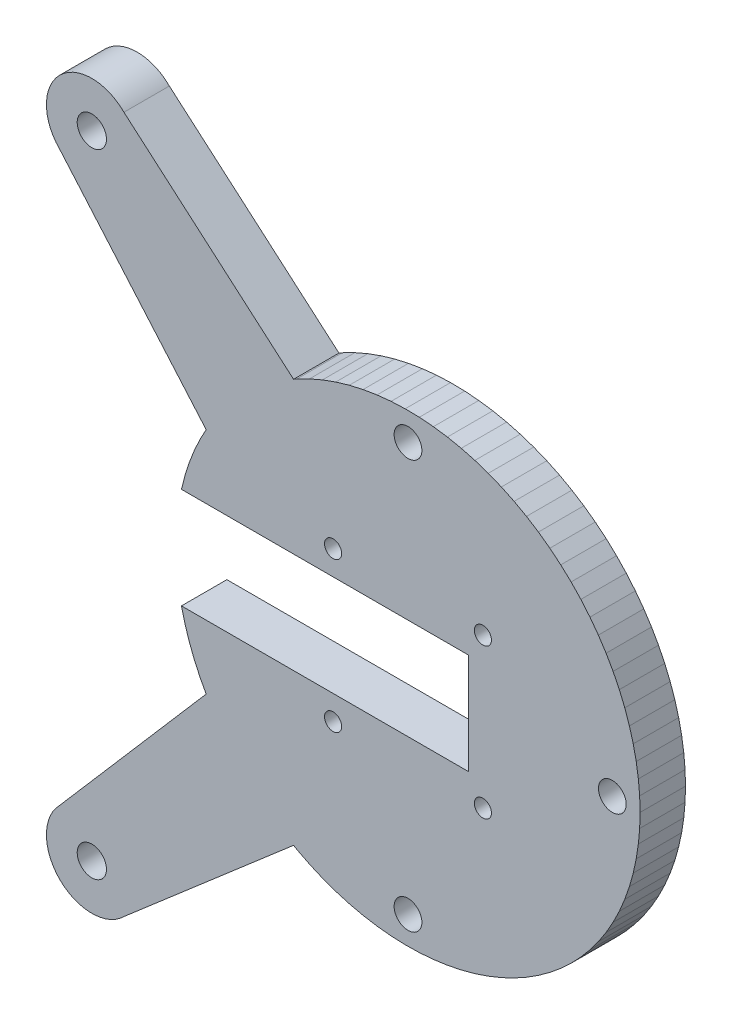
SolidWorks part; units mm, degrees
ref_plane "前视基准面" through (0, 0, 0) normal (0, 0, 1) x (1, 0, 0)
ref_plane "上视基准面" through (0, 0, 0) normal (0, 1, 0) x (1, 0, 0)
ref_plane "右视基准面" through (0, 0, 0) normal (1, 0, 0) x (0, 0, -1)
other "Configuration Table"
sketch "草图1" plane through (0, 0, 0) normal (0, 0, 1) x (1, 0, 0)
  line L0 (-44.8999, -10) -> (-44.2082, -12.7135)
  line L1 (-44.2082, -12.7135) -> (-43.3527, -15.3799)
  line L2 (-43.3527, -15.3799) -> (-42.3366, -17.9892)
  line L3 (-42.3366, -17.9892) -> (-41.1636, -20.532)
  line L4 (-41.1636, -20.532) -> (-39.838, -22.9986)
  line L5 (-39.838, -22.9986) -> (-38.3648, -25.38)
  line L6 (-38.3648, -25.38) -> (-36.7494, -27.6673)
  line L7 (-36.7494, -27.6673) -> (-34.9978, -29.8521)
  line L8 (-34.9978, -29.8521) -> (-33.1166, -31.9263)
  line L9 (-33.1166, -31.9263) -> (-31.1126, -33.8822)
  line L10 (-31.1126, -33.8822) -> (-28.9933, -35.7125)
  line L11 (-28.9933, -35.7125) -> (-26.7666, -37.4105)
  line L12 (-26.7666, -37.4105) -> (-24.4407, -38.9699)
  line L13 (-24.4407, -38.9699) -> (-22.0242, -40.3848)
  line L14 (-22.0242, -40.3848) -> (-19.5261, -41.6501)
  line L15 (-19.5261, -41.6501) -> (-16.9557, -42.761)
  line L16 (-16.9557, -42.761) -> (-14.3224, -43.7135)
  line L17 (-14.3224, -43.7135) -> (-11.636, -44.504)
  line L18 (-11.636, -44.504) -> (-8.9066, -45.1295)
  line L19 (-8.9066, -45.1295) -> (-6.1441, -45.5878)
  line L20 (-6.1441, -45.5878) -> (-3.3588, -45.8772)
  line L21 (-3.3588, -45.8772) -> (-0.5611, -45.9966)
  line L22 (-0.5611, -45.9966) -> (2.2387, -45.9455)
  line L23 (2.2387, -45.9455) -> (5.0302, -45.7241)
  line L24 (5.0302, -45.7241) -> (7.803, -45.3334)
  line L25 (7.803, -45.3334) -> (10.5469, -44.7746)
  line L26 (10.5469, -44.7746) -> (13.2518, -44.0499)
  line L27 (13.2518, -44.0499) -> (15.9075, -43.1619)
  line L28 (15.9075, -43.1619) -> (18.5043, -42.114)
  line L29 (18.5043, -42.114) -> (21.0325, -40.9101)
  line L30 (21.0325, -40.9101) -> (23.4828, -39.5545)
  line L31 (23.4828, -39.5545) -> (25.8461, -38.0523)
  line L32 (25.8461, -38.0523) -> (28.1135, -36.4092)
  line L33 (28.1135, -36.4092) -> (30.2768, -34.6311)
  line L34 (30.2768, -34.6311) -> (32.3279, -32.7247)
  line L35 (32.3279, -32.7247) -> (34.2592, -30.697)
  line L36 (34.2592, -30.697) -> (36.0636, -28.5556)
  line L37 (36.0636, -28.5556) -> (37.7342, -26.3083)
  line L38 (37.7342, -26.3083) -> (39.2651, -23.9635)
  line L39 (39.2651, -23.9635) -> (40.6505, -21.53)
  line L40 (40.6505, -21.53) -> (41.8852, -19.0166)
  line L41 (41.8852, -19.0166) -> (42.9647, -16.4328)
  line L42 (42.9647, -16.4328) -> (43.8849, -13.7881)
  line L43 (43.8849, -13.7881) -> (44.6426, -11.0923)
  line L44 (44.6426, -11.0923) -> (45.2348, -8.3554)
  line L45 (45.2348, -8.3554) -> (45.6594, -5.5875)
  line L46 (45.6594, -5.5875) -> (45.9148, -2.799)
  line L47 (45.9148, -2.799) -> (46, 0)
  line L48 (46, 0) -> (45.9148, 2.799)
  line L49 (45.9148, 2.799) -> (45.6594, 5.5875)
  line L50 (45.6594, 5.5875) -> (45.2348, 8.3554)
  line L51 (45.2348, 8.3554) -> (44.6426, 11.0923)
  line L52 (44.6426, 11.0923) -> (43.8849, 13.7881)
  line L53 (43.8849, 13.7881) -> (42.9647, 16.4328)
  line L54 (42.9647, 16.4328) -> (41.8852, 19.0166)
  line L55 (41.8852, 19.0166) -> (40.6505, 21.53)
  line L56 (40.6505, 21.53) -> (39.2651, 23.9635)
  line L57 (39.2651, 23.9635) -> (37.7342, 26.3083)
  line L58 (37.7342, 26.3083) -> (36.0636, 28.5556)
  line L59 (36.0636, 28.5556) -> (34.2592, 30.697)
  line L60 (34.2592, 30.697) -> (32.3279, 32.7247)
  line L61 (32.3279, 32.7247) -> (30.2768, 34.6311)
  line L62 (30.2768, 34.6311) -> (28.1135, 36.4092)
  line L63 (28.1135, 36.4092) -> (25.8461, 38.0523)
  line L64 (25.8461, 38.0523) -> (23.4828, 39.5545)
  line L65 (23.4828, 39.5545) -> (21.0325, 40.9101)
  line L66 (21.0325, 40.9101) -> (18.5043, 42.114)
  line L67 (18.5043, 42.114) -> (15.9075, 43.1619)
  line L68 (15.9075, 43.1619) -> (13.2518, 44.0499)
  line L69 (13.2518, 44.0499) -> (10.5469, 44.7746)
  line L70 (10.5469, 44.7746) -> (7.803, 45.3334)
  line L71 (7.803, 45.3334) -> (5.0302, 45.7241)
  line L72 (5.0302, 45.7241) -> (2.2387, 45.9455)
  line L73 (2.2387, 45.9455) -> (-0.5611, 45.9966)
  line L74 (-0.5611, 45.9966) -> (-3.3588, 45.8772)
  line L75 (-3.3588, 45.8772) -> (-6.1441, 45.5878)
  line L76 (-6.1441, 45.5878) -> (-8.9066, 45.1295)
  line L77 (-8.9066, 45.1295) -> (-11.636, 44.504)
  line L78 (-11.636, 44.504) -> (-14.3224, 43.7135)
  line L79 (-14.3224, 43.7135) -> (-16.9557, 42.761)
  line L80 (-16.9557, 42.761) -> (-19.5261, 41.6501)
  line L81 (-19.5261, 41.6501) -> (-22.0242, 40.3848)
  line L82 (-22.0242, 40.3848) -> (-24.4407, 38.9699)
  line L83 (-24.4407, 38.9699) -> (-26.7666, 37.4105)
  line L84 (-26.7666, 37.4105) -> (-28.9933, 35.7125)
  line L85 (-28.9933, 35.7125) -> (-31.1126, 33.8822)
  line L86 (-31.1126, 33.8822) -> (-33.1166, 31.9263)
  line L87 (-33.1166, 31.9263) -> (-34.9978, 29.8521)
  line L88 (-34.9978, 29.8521) -> (-36.7494, 27.6673)
  line L89 (-36.7494, 27.6673) -> (-38.3648, 25.38)
  line L90 (-38.3648, 25.38) -> (-39.838, 22.9986)
  line L91 (-39.838, 22.9986) -> (-41.1636, 20.532)
  line L92 (-41.1636, 20.532) -> (-42.3366, 17.9892)
  line L93 (-42.3366, 17.9892) -> (-43.3527, 15.3799)
  line L94 (-43.3527, 15.3799) -> (-44.2082, 12.7135)
  line L95 (-44.2082, 12.7135) -> (-44.8999, 10)
  line L96 (-44.8999, 10) -> (12, 10)
  line L97 (12, 10) -> (12, -10)
  line L98 (12, -10) -> (-44.8999, -10)
  circle A0 centre (-14.845, -14.845) radius 3.75
  circle A1 centre (-14.845, 14.845) radius 3.75
  circle A2 centre (14.845, -14.845) radius 3.75
  circle A3 centre (14.845, 14.845) radius 3.75
  circle A4 centre (0, -40.5) radius 2.75
  circle A5 centre (0, 40.5) radius 2.75
  circle A6 centre (40.5, 0) radius 2.75
extrude "底层与螺钉头避空" add sketch "草图1" along normal blind 4 from offset 0
sketch "草图2" plane through (0, 0, 0) normal (0, 0, 1) x (1, 0, 0)
  line L0 (-44.8999, -10) -> (-44.2082, -12.7135)
  line L1 (-44.2082, -12.7135) -> (-43.3527, -15.3799)
  line L2 (-43.3527, -15.3799) -> (-42.3366, -17.9892)
  line L3 (-42.3366, -17.9892) -> (-41.1636, -20.532)
  line L4 (-41.1636, -20.532) -> (-39.838, -22.9986)
  line L5 (-39.838, -22.9986) -> (-38.3648, -25.38)
  line L6 (-38.3648, -25.38) -> (-36.7494, -27.6673)
  line L7 (-36.7494, -27.6673) -> (-34.9978, -29.8521)
  line L8 (-34.9978, -29.8521) -> (-33.1166, -31.9263)
  line L9 (-33.1166, -31.9263) -> (-31.1126, -33.8822)
  line L10 (-31.1126, -33.8822) -> (-28.9933, -35.7125)
  line L11 (-28.9933, -35.7125) -> (-26.7666, -37.4105)
  line L12 (-26.7666, -37.4105) -> (-24.4407, -38.9699)
  line L13 (-24.4407, -38.9699) -> (-22.0242, -40.3848)
  line L14 (-22.0242, -40.3848) -> (-19.5261, -41.6501)
  line L15 (-19.5261, -41.6501) -> (-16.9557, -42.761)
  line L16 (-16.9557, -42.761) -> (-14.3224, -43.7135)
  line L17 (-14.3224, -43.7135) -> (-11.636, -44.504)
  line L18 (-11.636, -44.504) -> (-8.9066, -45.1295)
  line L19 (-8.9066, -45.1295) -> (-6.1441, -45.5878)
  line L20 (-6.1441, -45.5878) -> (-3.3588, -45.8772)
  line L21 (-3.3588, -45.8772) -> (-0.5611, -45.9966)
  line L22 (-0.5611, -45.9966) -> (2.2387, -45.9455)
  line L23 (2.2387, -45.9455) -> (5.0302, -45.7241)
  line L24 (5.0302, -45.7241) -> (7.803, -45.3334)
  line L25 (7.803, -45.3334) -> (10.5469, -44.7746)
  line L26 (10.5469, -44.7746) -> (13.2518, -44.0499)
  line L27 (13.2518, -44.0499) -> (15.9075, -43.1619)
  line L28 (15.9075, -43.1619) -> (18.5043, -42.114)
  line L29 (18.5043, -42.114) -> (21.0325, -40.9101)
  line L30 (21.0325, -40.9101) -> (23.4828, -39.5545)
  line L31 (23.4828, -39.5545) -> (25.8461, -38.0523)
  line L32 (25.8461, -38.0523) -> (28.1135, -36.4092)
  line L33 (28.1135, -36.4092) -> (30.2768, -34.6311)
  line L34 (30.2768, -34.6311) -> (32.3279, -32.7247)
  line L35 (32.3279, -32.7247) -> (34.2592, -30.697)
  line L36 (34.2592, -30.697) -> (36.0636, -28.5556)
  line L37 (36.0636, -28.5556) -> (37.7342, -26.3083)
  line L38 (37.7342, -26.3083) -> (39.2651, -23.9635)
  line L39 (39.2651, -23.9635) -> (40.6505, -21.53)
  line L40 (40.6505, -21.53) -> (41.8852, -19.0166)
  line L41 (41.8852, -19.0166) -> (42.9647, -16.4328)
  line L42 (42.9647, -16.4328) -> (43.8849, -13.7881)
  line L43 (43.8849, -13.7881) -> (44.6426, -11.0923)
  line L44 (44.6426, -11.0923) -> (45.2348, -8.3554)
  line L45 (45.2348, -8.3554) -> (45.6594, -5.5875)
  line L46 (45.6594, -5.5875) -> (45.9148, -2.799)
  line L47 (45.9148, -2.799) -> (46, 0)
  line L48 (46, 0) -> (45.9148, 2.799)
  line L49 (45.9148, 2.799) -> (45.6594, 5.5875)
  line L50 (45.6594, 5.5875) -> (45.2348, 8.3554)
  line L51 (45.2348, 8.3554) -> (44.6426, 11.0923)
  line L52 (44.6426, 11.0923) -> (43.8849, 13.7881)
  line L53 (43.8849, 13.7881) -> (42.9647, 16.4328)
  line L54 (42.9647, 16.4328) -> (41.8852, 19.0166)
  line L55 (41.8852, 19.0166) -> (40.6505, 21.53)
  line L56 (40.6505, 21.53) -> (39.2651, 23.9635)
  line L57 (39.2651, 23.9635) -> (37.7342, 26.3083)
  line L58 (37.7342, 26.3083) -> (36.0636, 28.5556)
  line L59 (36.0636, 28.5556) -> (34.2592, 30.697)
  line L60 (34.2592, 30.697) -> (32.3279, 32.7247)
  line L61 (32.3279, 32.7247) -> (30.2768, 34.6311)
  line L62 (30.2768, 34.6311) -> (28.1135, 36.4092)
  line L63 (28.1135, 36.4092) -> (25.8461, 38.0523)
  line L64 (25.8461, 38.0523) -> (23.4828, 39.5545)
  line L65 (23.4828, 39.5545) -> (21.0325, 40.9101)
  line L66 (21.0325, 40.9101) -> (18.5043, 42.114)
  line L67 (18.5043, 42.114) -> (15.9075, 43.1619)
  line L68 (15.9075, 43.1619) -> (13.2518, 44.0499)
  line L69 (13.2518, 44.0499) -> (10.5469, 44.7746)
  line L70 (10.5469, 44.7746) -> (7.803, 45.3334)
  line L71 (7.803, 45.3334) -> (5.0302, 45.7241)
  line L72 (5.0302, 45.7241) -> (2.2387, 45.9455)
  line L73 (2.2387, 45.9455) -> (-0.5611, 45.9966)
  line L74 (-0.5611, 45.9966) -> (-3.3588, 45.8772)
  line L75 (-3.3588, 45.8772) -> (-6.1441, 45.5878)
  line L76 (-6.1441, 45.5878) -> (-8.9066, 45.1295)
  line L77 (-8.9066, 45.1295) -> (-11.636, 44.504)
  line L78 (-11.636, 44.504) -> (-14.3224, 43.7135)
  line L79 (-14.3224, 43.7135) -> (-16.9557, 42.761)
  line L80 (-16.9557, 42.761) -> (-19.5261, 41.6501)
  line L81 (-19.5261, 41.6501) -> (-22.0242, 40.3848)
  line L82 (-22.0242, 40.3848) -> (-24.4407, 38.9699)
  line L83 (-24.4407, 38.9699) -> (-26.7666, 37.4105)
  line L84 (-26.7666, 37.4105) -> (-28.9933, 35.7125)
  line L85 (-28.9933, 35.7125) -> (-31.1126, 33.8822)
  line L86 (-31.1126, 33.8822) -> (-33.1166, 31.9263)
  line L87 (-33.1166, 31.9263) -> (-34.9978, 29.8521)
  line L88 (-34.9978, 29.8521) -> (-36.7494, 27.6673)
  line L89 (-36.7494, 27.6673) -> (-38.3648, 25.38)
  line L90 (-38.3648, 25.38) -> (-39.838, 22.9986)
  line L91 (-39.838, 22.9986) -> (-41.1636, 20.532)
  line L92 (-41.1636, 20.532) -> (-42.3366, 17.9892)
  line L93 (-42.3366, 17.9892) -> (-43.3527, 15.3799)
  line L94 (-43.3527, 15.3799) -> (-44.2082, 12.7135)
  line L95 (-44.2082, 12.7135) -> (-44.8999, 10)
  line L96 (-44.8999, 10) -> (12, 10)
  line L97 (12, 10) -> (12, -10)
  line L98 (12, -10) -> (-44.8999, -10)
  circle A0 centre (-14.845, -14.845) radius 1.7
  circle A1 centre (-14.845, 14.845) radius 1.7
  circle A2 centre (14.845, -14.845) radius 1.7
  circle A3 centre (14.845, 14.845) radius 1.7
  circle A4 centre (0, -40.5) radius 2.75
  circle A5 centre (0, 40.5) radius 2.75
  circle A6 centre (40.5, 0) radius 2.75
extrude "上层与通孔" add sketch "草图2" along normal blind 5 from offset 4
sketch "草图3" plane through (0, 0, 0) normal (0, 0, 1) x (1, 0, 0)
  line L0 (-33.234, -14.8492) -> (-69.029, -56.301)
  line L1 (-56.301, -69.029) -> (-14.8492, -33.234)
  line L2 (-14.8492, -33.234) -> (-33.234, -14.8492)
  arc A0 (-69.029, -56.301) -> (-56.301, -69.029) centre (-62.665, -62.665) ccw
  circle A1 centre (-62.665, -62.665) radius 2.9
extrude "左工作台安装耳_通孔5.8" add sketch "草图3" along normal blind 9 from offset 0
sketch "草图4" plane through (0, 0, 0) normal (0, 0, 1) x (1, 0, 0)
  line L0 (-14.8492, 33.234) -> (-56.301, 69.029)
  line L1 (-69.029, 56.301) -> (-33.234, 14.8492)
  line L2 (-33.234, 14.8492) -> (-14.8492, 33.234)
  arc A0 (-56.301, 69.029) -> (-69.029, 56.301) centre (-62.665, 62.665) ccw
  circle A1 centre (-62.665, 62.665) radius 2.9
extrude "右工作台安装耳_通孔5.8" add sketch "草图4" along normal blind 9 from offset 0
